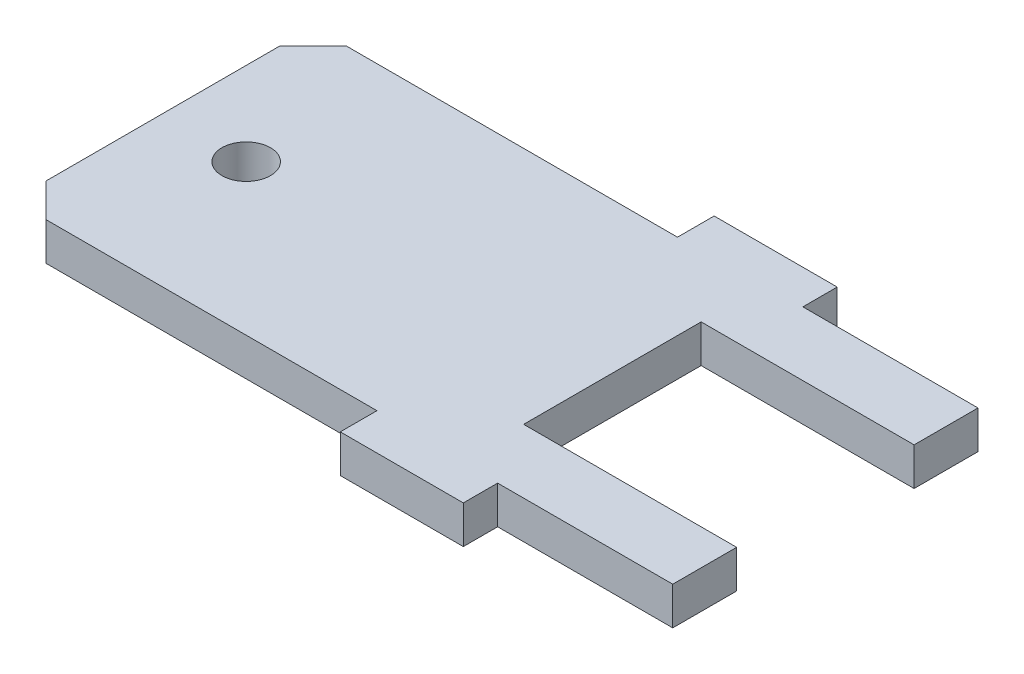
SolidWorks part; units mm, degrees
ref_plane "Спереди" through (0, 0, 0) normal (0, 0, 1) x (1, 0, 0)
ref_plane "Сверху" through (0, 0, 0) normal (0, 1, 0) x (1, 0, 0)
ref_plane "Справа" through (0, 0, 0) normal (1, 0, 0) x (0, 0, -1)
sketch "Эскиз1" plane through (0, 0, 0) normal (0, 1, 0) x (1, 0, 0)
  line L0 (0, -2.4679) -> (0, 2.4679)
  line L1 (0, 2.4679) -> (0.7071, 3.175)
  line L2 (0.7071, 3.175) -> (7.7, 3.175)
  line L3 (7.7, 3.175) -> (7.7, 3.95)
  line L4 (7.7, 3.95) -> (10.3, 3.95)
  line L5 (10.3, 3.95) -> (10.3, 3.225)
  line L6 (10.3, 3.225) -> (14, 3.225)
  line L7 (14, 3.225) -> (14, 1.875)
  line L8 (14, 1.875) -> (9.5, 1.875)
  line L9 (9.5, 1.875) -> (9.5, -1.875)
  line L10 (9.5, 0) -> (0, 0) construction
  line L11 (14, -1.875) -> (9.5, -1.875)
  line L12 (14, -3.225) -> (14, -1.875)
  line L13 (10.3, -3.225) -> (14, -3.225)
  line L14 (10.3, -3.95) -> (10.3, -3.225)
  line L15 (7.7, -3.95) -> (10.3, -3.95)
  line L16 (7.7, -3.175) -> (7.7, -3.95)
  line L17 (0.7071, -3.175) -> (7.7, -3.175)
  line L18 (0, -2.4679) -> (0.7071, -3.175)
  circle A0 centre (1.7619, 0) radius 0.5124
  dimension "D1" = 7.7
  dimension "D2" = 3.175
  dimension "D3" = 1
  dimension "D4" = 3.95
  dimension "D5" = 3.7
  dimension "D6" = 1.875
  dimension "D7" = 3.225
  dimension "D8" = 14
  dimension "D9" = 4.5
extrude "Бобышка-Вытянуть1" add sketch "Эскиз1" along normal mid plane 0.8
sketch "Эскиз2" plane through (14, 0, 0) normal (1, 0, 0) x (0, 0, -1)
  line L0 (-1.875, 0.4) -> (-1.875, -0.4) construction
  line L1 (3.225, 0.4) -> (3.225, -0.4) construction
  line L2 (1.875, 0.4) -> (3.225, 0.4) construction
  line L3 (-3.225, 0.4) -> (-1.875, 0.4) construction
  point P0 (2.55, 0)
  point P1 (-2.55, 0)
  point P4 (-1.875, 0)
  point P7 (3.225, 0)
  point P12 (0, 0)
  dimension "D1" = 0.675
  dimension "D2" = 0.675
  dimension "D3" = 0.4
  dimension "D4" = 0.4
sketch "Эскиз3" plane through (0, 0, 0) normal (-1, 0, 0) x (0, 0, 1)
  point P0 (-2.55, 0)
  point P1 (2.55, 0)
sketch "Эскиз4" plane through (0, 0, 0) normal (0, 1, 0) x (1, 0, 0)
  line L0 (0, -2.55) -> (14, -2.55) construction
  line L2 (0, 2.55) -> (14, 2.55) construction
